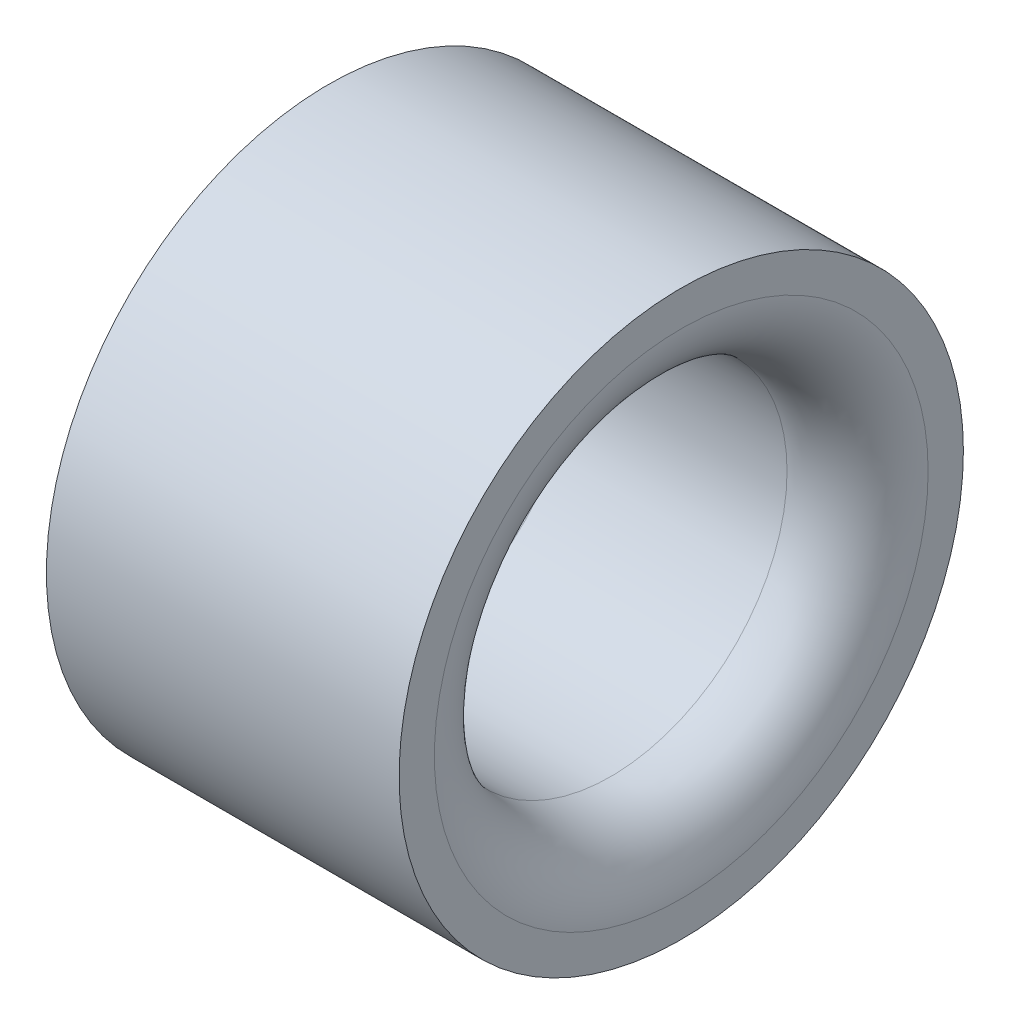
SolidWorks part; units mm, degrees
ref_plane "Front Plane" through (0, 0, 0) normal (0, 0, 1) x (1, 0, 0)
ref_plane "Top Plane" through (0, 0, 0) normal (0, 1, 0) x (1, 0, 0)
ref_plane "Right Plane" through (0, 0, 0) normal (1, 0, 0) x (0, 0, -1)
sketch "Sketch1" plane through (0, 0, 0) normal (1, 0, 0) x (0, 0, -1)
  circle A0 centre (0, 0) radius 4
  circle A1 centre (0, 0) radius 2.5
  dimension "D1" = 8
  dimension "D2" = 5
extrude "Boss-Extrude1" add sketch "Sketch1" along normal blind 5
fillet "Fillet2" radius 1 2 edges at (0, 0, -2.5) (5, 0, -2.5)
